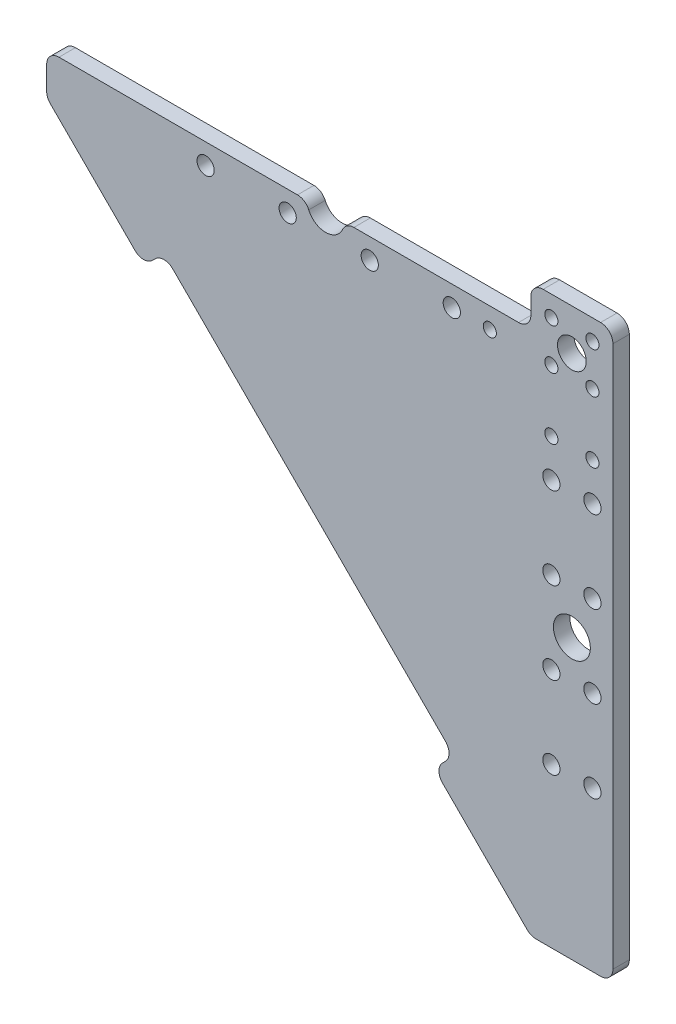
SolidWorks part; units mm, degrees
material "Thornel Mat VMA"
ref_plane "前视基准面" through (0, 0, 0) normal (0, 0, 1) x (1, 0, 0)
ref_plane "上视基准面" through (0, 0, 0) normal (0, 1, 0) x (1, 0, 0)
ref_plane "右视基准面" through (0, 0, 0) normal (1, 0, 0) x (0, 0, -1)
other "Configuration Table"
sketch "草图1" plane through (0, 0, 0) normal (0, 0, 1) x (1, 0, 0)
  line L0 (-128, -10) -> (-10, -128)
  line L5 (-10, 10) -> (10, 10)
  line L6 (-10, 10) -> (-10, -10)
  line L11 (-10, -10) -> (10, -10)
  line L12 (10, 10) -> (10, -10)
  line L13 (-10, 10) -> (10, -10) construction
  line L14 (-10, -10) -> (10, 10) construction
  line L15 (-10, -128) -> (10, -128)
  line L16 (-10, -128) -> (-10, -10)
  line L17 (-10, -10) -> (10, -10)
  line L18 (10, -128) -> (10, -10)
  line L19 (-10, -128) -> (10, -10) construction
  line L20 (-10, -10) -> (10, -128) construction
  line L21 (-128, 10) -> (-10, 10)
  line L22 (-128, 10) -> (-128, -10)
  line L23 (-128, -10) -> (-10, -10)
  line L24 (-10, 10) -> (-10, -10)
  line L25 (-128, 10) -> (-10, -10) construction
  line L26 (-128, -10) -> (-10, 10) construction
  point P0 (0, 0)
  point P6 (0, -69)
  point P7 (-69, 0)
  dimension "D1" = 20
  dimension "D2" = 20
  dimension "D3" = 118
  dimension "D4" = 118
extrude "凸台-拉伸1" add sketch "草图1" along normal blind 4 contours L22 L23 L6 L21 | L12 L5 L6 L11 | L15 L18 L11 L16 | L23 L0 L16
sketch "草图3" plane through (0, 0, 4) normal (0, 0, 1) x (1, 0, 0)
  line L1 (-5, 5) -> (5, 5) construction
  line L2 (-5, 5) -> (-5, -5) construction
  line L3 (-5, -5) -> (5, -5) construction
  line L4 (5, 5) -> (5, -5) construction
  line L5 (-5, 5) -> (5, -5) construction
  line L6 (-5, -5) -> (5, 5) construction
  circle A0 centre (0, 0) radius 3.5
  circle A1 centre (5, 5) radius 1.6
  circle A2 centre (-5, 5) radius 1.6
  circle A3 centre (-5, -5) radius 1.6
  circle A4 centre (5, -5) radius 1.6
  circle A5 centre (-20, -5) radius 1.6
  circle A6 centre (-5, -20) radius 1.6
  circle A7 centre (5, -20) radius 1.6
  circle A8 centre (5, 20) radius 1.6
  circle A9 centre (-5, 20) radius 1.6
  circle A10 centre (20, -5) radius 1.6
  circle A11 centre (20, 5) radius 1.6
  circle A12 centre (-20, 5) radius 1.6
  dimension "D1" = 10
  dimension "D5" = 3.2
  dimension "D10" = 20
  dimension "D11" = 20
  dimension "D13" = 3.2
  dimension "D15" = 3.2
  dimension "D2" = 10
  dimension "D3" = 2
  dimension "D4" = 2
  dimension "D6" = 2
  dimension "D7" = 2
  dimension "D8" = 2
  dimension "D9" = 2
extrude "切除-拉伸1" cut sketch "草图3" against normal blind 4
sketch "草图4" plane through (0, 0, 4) normal (0, 0, 1) x (1, 0, 0)
  line L1 (-128, 10) -> (10, 10) construction
  circle A0 centre (0, -60) radius 4.5
  circle A1 centre (-5, -29.2639) radius 2.1
  circle A2 centre (5, -29.2639) radius 2.1
  circle A3 centre (5, -49.2639) radius 2.1
  circle A4 centre (5, -69.2639) radius 2.1
  circle A5 centre (5, -89.2639) radius 2.1
  circle A6 centre (-5, -49.2639) radius 2.1
  circle A7 centre (-5, -69.2639) radius 2.1
  circle A8 centre (-5, -89.2639) radius 2.1
  circle A9 centre (-89.2639, -5) radius 2.1
  circle A10 centre (-69.2639, -5) radius 2.1
  circle A11 centre (-49.2639, -5) radius 2.1
  circle A12 centre (-89.2639, 5) radius 2.1
  circle A13 centre (-69.2639, 5) radius 2.1
  circle A14 centre (-49.2639, 5) radius 2.1
  circle A15 centre (-29.2639, 5) radius 2.1
  circle A16 centre (-29.2639, -5) radius 2.1
  circle A17 centre (-60, 0) radius 4.5
  dimension "D1" = 60
  dimension "D4" = 5
  dimension "D5" = 4.2
  dimension "D6" = 10
  dimension "D7" = 5
  dimension "D2" = 2
  dimension "D3" = 4
extrude "切除-拉伸2" cut sketch "草图4" against normal blind 4
sketch "草图10" plane through (0, 0, 4) normal (0, 0, 1) x (1, 0, 0)
  line L0 (10, 10) -> (-69, -69) construction
  line L1 (-128, -10) -> (-10, -128) construction
  line L2 (-45.8776, -28.1999) -> (-38.8065, -21.1289) construction
  line L3 (-45.8776, -28.1999) -> (-28.1999, -45.8776) construction
  line L4 (-38.8065, -21.1289) -> (-21.1289, -38.8065) construction
  line L5 (-28.1999, -45.8776) -> (-21.1289, -38.8065) construction
  line L6 (-45.8776, -28.1999) -> (-21.1289, -38.8065) construction
  line L7 (-38.8065, -21.1289) -> (-28.1999, -45.8776) construction
  line L8 (-72.5497, -42.4976) -> (-66.8928, -36.8408) construction
  line L9 (-72.5497, -42.4976) -> (-42.4976, -72.5497) construction
  line L10 (-66.8928, -36.8408) -> (-36.8408, -66.8928) construction
  line L11 (-42.4976, -72.5497) -> (-36.8408, -66.8928) construction
  line L12 (-72.5497, -42.4976) -> (-36.8408, -66.8928) construction
  line L13 (-66.8928, -36.8408) -> (-42.4976, -72.5497) construction
  circle A0 centre (-36.8408, -66.8928) radius 1.5
  circle A1 centre (-42.4976, -72.5497) radius 1.5
  circle A2 centre (-72.5497, -42.4976) radius 1.5
  circle A3 centre (-66.8928, -36.8408) radius 1.5
  circle A4 centre (-28.1999, -45.8776) radius 2
  circle A5 centre (-21.1289, -38.8065) radius 2
  circle A6 centre (-38.8065, -21.1289) radius 2
  circle A7 centre (-45.8776, -28.1999) radius 2
  point P6 (-33.5032, -33.5032)
  point P7 (-54.6952, -54.6952)
  dimension "D7" = 3
  dimension "D8" = 4
  dimension "D1" = 25
  dimension "D2" = 10
  dimension "D3" = 45.2
  dimension "D4" = 42.5
  dimension "D5" = 8
  dimension "D6" = 29.97
extrude "切除-拉伸6" [suppressed] cut sketch "草图10" against normal blind 4
sketch "草图11" plane through (0, 0, 4) normal (0, 0, 1) x (1, 0, 0)
  line L0 (0, 0) -> (-69, -69)
  line L1 (-128, -10) -> (-10, -128) construction
  line L2 (-99.4056, -28.6949) -> (-104.3553, -33.6447)
  line L3 (-99.4056, -28.6949) -> (-28.6949, -99.4056)
  line L4 (-104.3553, -33.6447) -> (-33.6447, -104.3553)
  line L5 (-28.6949, -99.4056) -> (-33.6447, -104.3553)
  line L6 (-99.4056, -28.6949) -> (-33.6447, -104.3553) construction
  line L7 (-104.3553, -33.6447) -> (-28.6949, -99.4056) construction
  point P6 (-66.5251, -66.5251)
  line M40 (-128, -10) -> (-10, -128)
  dimension "D1" = 7
  dimension "D2" = 100
extrude "切除-拉伸7" cut sketch "草图11" against normal blind 4 contours L3 L2 L0 M40 | L5 L3 L0 M40
sketch "草图12" plane through (0, 0, 4) normal (0, 0, 1) x (1, 0, 0)
  line L0 (-128, 10) -> (-10, 10)
  line L1 (-128, 10) -> (-128, 0)
  line L2 (-10, 10) -> (-10, 0)
  line L3 (-128, 0) -> (-10, 0)
  line L4 (-128, 10) -> (10, 10) construction
  dimension "D1" = 10
  dimension "D2" = 118
extrude "切除-拉伸8" cut sketch "草图12" against normal blind 4
fillet "圆角3" radius 3 13 edges at (-128, -10, 2) (-104.3553, -33.6447, 2) (-99.4056, -28.6949, 2) (-28.6949, -99.4056, 2) (-33.6447, -104.3553, 2) (-10, -128, 2) (10, -128, 2) (10, 10, 2) (-55.5, 0, 2) (-64.5, 0, 2) (-128, 0, 2) (-10, 0, 2) (-10, 10, 2)
